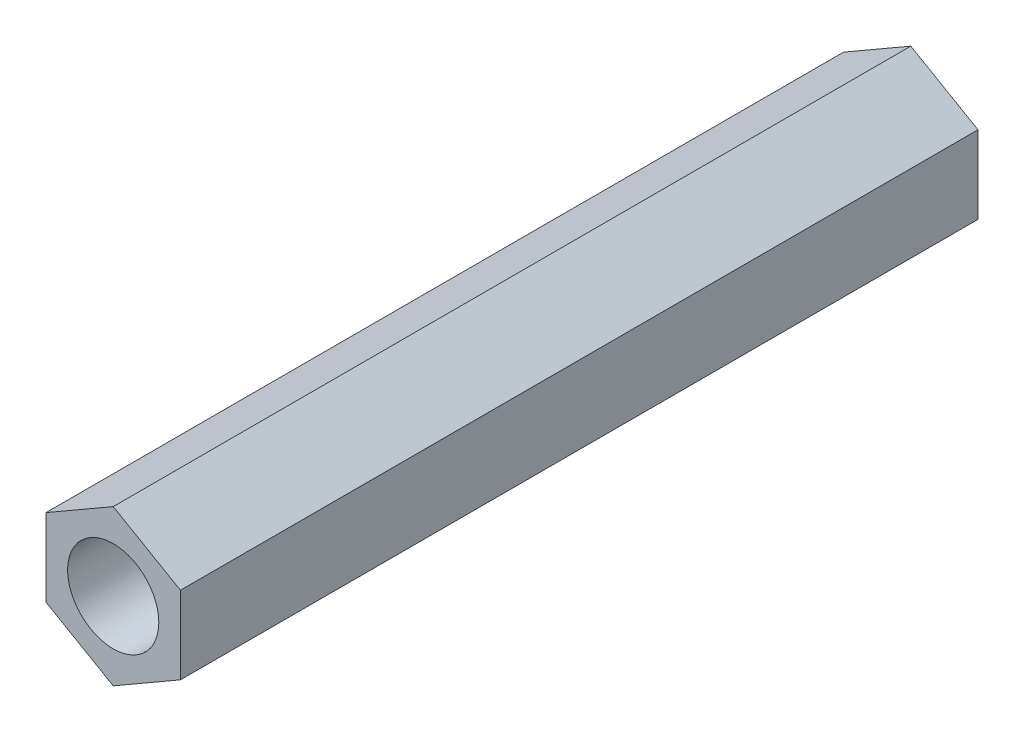
SolidWorks part; units mm, degrees
ref_plane "前视基准面" through (0, 0, 0) normal (0, 0, 1) x (1, 0, 0)
ref_plane "上视基准面" through (0, 0, 0) normal (0, 1, 0) x (1, 0, 0)
ref_plane "右视基准面" through (0, 0, 0) normal (1, 0, 0) x (0, 0, -1)
other "Configuration Table"
sketch "草图1" plane through (0, 0, 0) normal (0, 0, 1) x (1, 0, 0)
  line L1 (2.95, -1.7032) -> (2.95, 1.7032)
  line L2 (2.95, 1.7032) -> (0, 3.4064)
  line L3 (0, 3.4064) -> (-2.95, 1.7032)
  line L4 (-2.95, 1.7032) -> (-2.95, -1.7032)
  line L5 (-2.95, -1.7032) -> (0, -3.4064)
  line L6 (0, -3.4064) -> (2.95, -1.7032)
  circle A0 centre (0, 0) radius 2.95 construction
  circle A1 centre (0, 0) radius 2
  dimension "D2" = 4
  dimension "D1" = 5.9
extrude "凸台-拉伸1" add sketch "草图1" along normal blind 35
